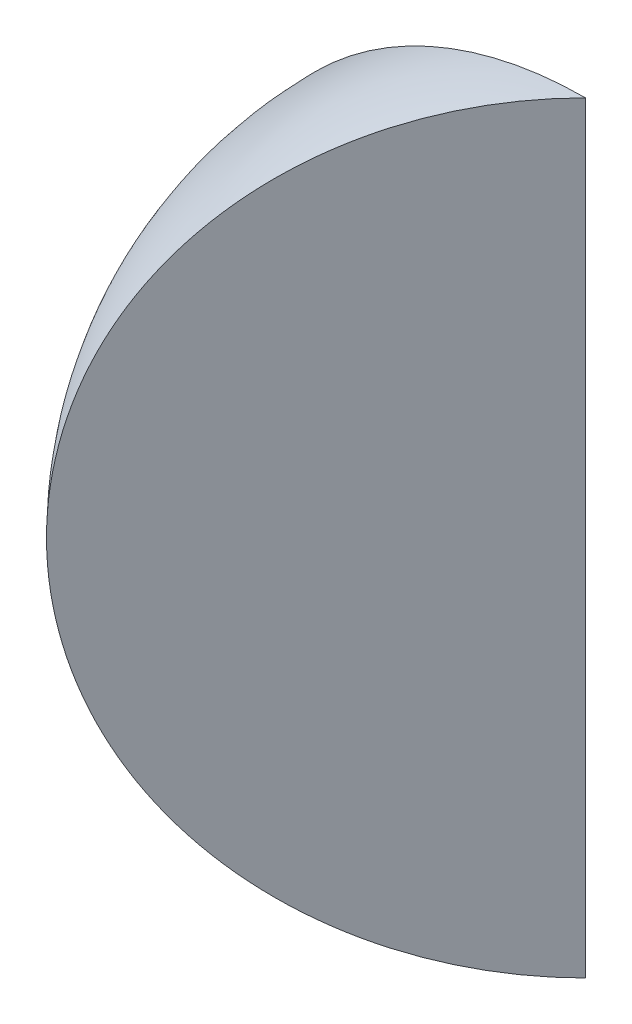
SolidWorks part; units mm, degrees
ref_plane "Front Plane" through (0, 0, 0) normal (0, 0, 1) x (1, 0, 0)
ref_plane "Top Plane" through (0, 0, 0) normal (0, 1, 0) x (1, 0, 0)
ref_plane "Right Plane" through (0, 0, 0) normal (1, 0, 0) x (0, 0, -1)
sketch "Sketch1" plane through (0, 0, 0) normal (0, 1, 0) x (1, 0, 0)
  line L0 (-29, 0) -> (0, 0)
  line L1 (0, 0) -> (29, 0)
  arc A0 (29, 0) -> (-29, 0) centre (0, 0) ccw
  dimension "D1" = 29
revolve "Revolve1" add sketch "Sketch1" angle 360 about L1
sketch "Sketch2" plane through (0, 0, 0) normal (0, 1, 0) x (1, 0, 0)
  line L0 (0, 0) -> (-31, 0)
  line L1 (0, 0) -> (-21.9203, -21.9203)
  arc A0 (-21.9203, -21.9203) -> (-31, 0) centre (0, 0) ccw
  circle A1 centre (0, 0) radius 29 construction
  dimension "D1" = 45
  dimension "D2" = 2
extrude "Cut-Extrude1" cut sketch "Sketch2" along normal through all both and the other way through all
